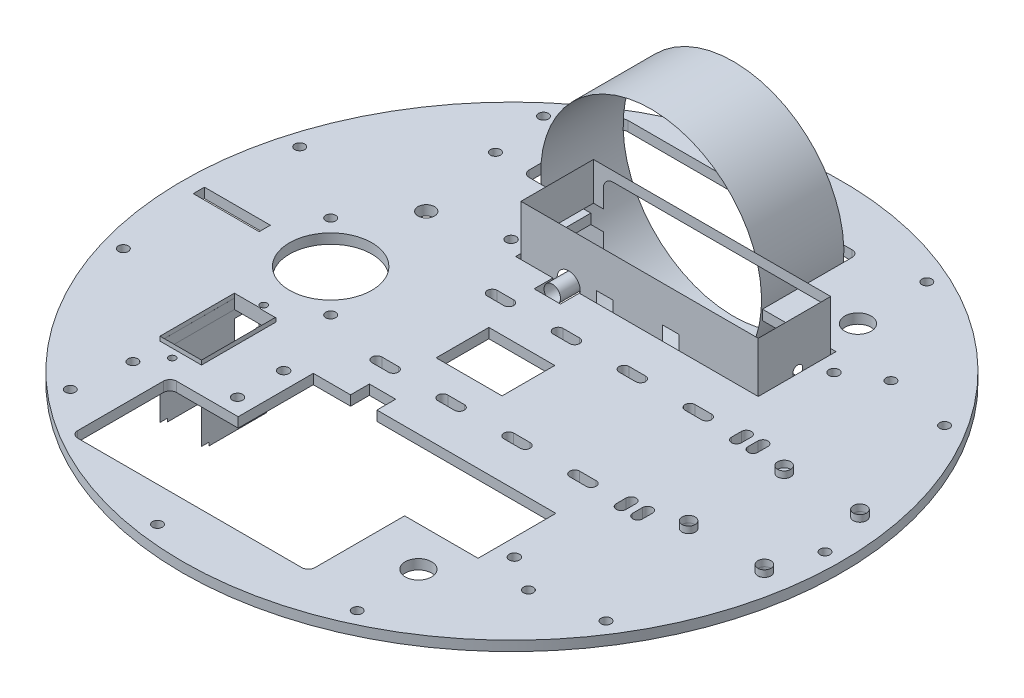
SolidWorks part; units mm, degrees
ref_plane "前基準面" through (0, 0, 0) normal (0, 0, 1) x (1, 0, 0)
ref_plane "上基準面" through (0, 0, 0) normal (0, 1, 0) x (1, 0, 0)
ref_plane "右基準面" through (0, 0, 0) normal (1, 0, 0) x (0, 0, -1)
sketch "草圖2" plane through (0, 0, 0) normal (0, 1, 0) x (1, 0, 0)
  line L1 (-60, 60) -> (60, 60) construction
  line L2 (-60, 60) -> (-60, -60) construction
  line L3 (-60, -60) -> (60, -60) construction
  line L4 (60, 60) -> (60, -60) construction
  line L5 (-60, 60) -> (60, -60) construction
  line L6 (-60, -60) -> (60, 60) construction
  circle A1 centre (0, 0) radius 100
  point P0 (0, 0)
  dimension "D1" = 120
  dimension "D3" = 200
  dimension "D2" = 120
extrude "填料-伸長1" add sketch "草圖2" along normal blind 3
sketch "草圖4" plane through (0, 3, 0) normal (0, 1, 0) x (1, 0, 0)
  line L0 (0, 0) -> (-55, 0) construction
  circle A1 centre (-55, 0) radius 12.5
  dimension "D2" = 25
  dimension "D1" = 55
extrude "除料-伸長2" cut sketch "草圖4" against normal blind 3
sketch "草圖5" plane through (0, 3, 0) normal (0, 1, 0) x (1, 0, 0)
  line L1 (-60, 55) -> (60, 55) construction
  line L2 (-60, 55) -> (-60, -55) construction
  line L3 (-60, -55) -> (60, -55) construction
  line L4 (60, 55) -> (60, -55) construction
  line L5 (-60, 55) -> (60, -55) construction
  line L6 (-60, -55) -> (60, 55) construction
  circle A0 centre (-60, 55) radius 1.5
  circle A1 centre (-60, -55) radius 1.5
  circle A2 centre (60, -55) radius 1.5
  circle A3 centre (60, 55) radius 1.5
  point P0 (0, 0)
  dimension "D3" = 3
  dimension "D4" = 3
  dimension "D5" = 3
  dimension "D6" = 3
  dimension "D1" = 120
  dimension "D2" = 110
extrude "除料-伸長3" cut sketch "草圖5" against normal blind 3
sketch "草圖6" plane through (0, 3, 0) normal (0, 1, 0) x (1, 0, 0)
  line L0 (0, 0) -> (126.0142, -2.0364) construction
  circle A0 centre (40, 65) radius 4
  circle A1 centre (37.8789, -66.2585) radius 4
  dimension "D1" = 8
  dimension "D2" = 40
  dimension "D3" = 65
extrude "除料-伸長4" cut sketch "草圖6" against normal blind 10
sketch "草圖7" plane through (0, 3, 0) normal (0, 1, 0) x (1, 0, 0)
  line L0 (0, 0) -> (-120.1853, 0) construction
  circle A1 centre (-70, -43.1259) radius 2.3
  circle A2 centre (-70, 43.1259) radius 2.3
  dimension "D1" = 43.1259
  dimension "D2" = 43.1259
  dimension "D3" = 70
extrude "除料-伸長5" [suppressed] cut sketch "草圖7" against normal up to surface (3 mm away)
sketch "草圖8" plane through (0, 3, 0) normal (0, 1, 0) x (1, 0, 0)
  line L0 (0, 0) -> (-129.4635, 0) construction
  line L2 (-99.2157, 12.5) -> (-111.2157, 12.5)
  line L3 (-99.2157, 12.5) -> (-99.2157, -12.5)
  line L4 (-99.2157, -12.5) -> (-111.2157, -12.5)
  line L5 (-114.2157, 9.5) -> (-114.2157, -9.5)
  circle A0 centre (0, 0) radius 100 construction
  arc A1 (-111.2157, -12.5) -> (-114.2157, -9.5) centre (-111.2157, -9.5) cw
  arc A2 (-111.2157, 12.5) -> (-114.2157, 9.5) centre (-111.2157, 9.5) ccw
  point P13 (-114.2157, -12.5)
  point P16 (-114.2157, 12.5)
  dimension "D3" = 3
  dimension "D1" = 25
  dimension "D2" = 15
extrude "填料-伸長2" add sketch "草圖8" against normal up to surface (3 mm away) up to face at (40, 0, -61)
sketch "草圖9" plane through (0, 3, 0) normal (0, 1, 0) x (1, 0, 0)
  line L0 (0, 0) -> (-116.8069, 0) construction
  line L2 (-95, 1.7) -> (-75, 1.7)
  line L3 (-95, 1.7) -> (-95, -1.7)
  line L4 (-95, -1.7) -> (-75, -1.7)
  line L5 (-75, 1.7) -> (-75, -1.7)
  line L6 (-95, 1.7) -> (-75, -1.7) construction
  line L7 (-95, -1.7) -> (-75, 1.7) construction
  point P3 (-85, 0)
  dimension "D1" = 3.4
  dimension "D2" = 20
  dimension "D3" = 75
extrude "除料-伸長6" cut sketch "草圖9" against normal up to surface (3 mm away) up to face at (40, 0, -61)
sketch "草圖11" plane through (0, 3, 0) normal (0, 1, 0) x (1, 0, 0)
  line L0 (-114.2157, 0) -> (0, 0) construction
  line L1 (-114.2157, 9.5) -> (-114.2157, -9.5) construction
  line L2 (-55, 12.5) -> (-55, -12.5) construction
  circle A0 centre (-55, 0) radius 12.5 construction
  circle A1 centre (-55, -29) radius 2.5
  circle A2 centre (-55, 29) radius 2.5
  dimension "D1" = 5
  dimension "D2" = 29
  dimension "D3" = 0
extrude "除料-伸長9" cut sketch "草圖11" against normal blind 10
sketch "草圖12" plane through (0, 3, 0) normal (0, 1, 0) x (1, 0, 0)
  circle A0 centre (0, 0) radius 100
  circle A1 centre (0, 0) radius 174.0467
extrude "除料-伸長10" cut sketch "草圖12" against normal blind 10
surface "曲面-偏移1" parameters "D1"=0
sketch "草圖13" plane through (0, 3, 0) normal (0, 1, 0) x (1, 0, 0)
  line L0 (43.2344, 53.5) -> (43.2344, 31.5) construction
  line L1 (-28.7656, 53.5) -> (43.2344, 53.5) construction
  line L2 (-28.7656, 31.5) -> (-28.7656, 53.5) construction
  line L3 (43.2344, 31.5) -> (-28.7656, 31.5) construction
  line L4 (43.2344, 53.5) -> (43.2344, 31.5) construction
  line L5 (21.7344, 53.5) -> (43.2344, 53.5) construction
  line L6 (-28.7656, 31.5) -> (-28.7656, 53.5) construction
  line L7 (43.2344, 31.5) -> (-18.2656, 31.5) construction
  line L8 (-16.7656, 33.5) -> (-16.7656, 26.5) construction
  line L10 (-18.2656, 30.7) -> (-18.2656, 25)
  line L11 (-18.2656, 25) -> (-10.2656, 25)
  line L12 (-10.2656, 30.7) -> (-10.2656, 25)
  line L14 (19.2344, 81.5) -> (-47.7656, 81.5) construction
  line L15 (-50.2656, 53.5) -> (-29.5656, 53.5)
  line L16 (-50.2656, 53.5) -> (-50.2656, 83.5)
  line L17 (-50.2656, 83.5) -> (21.7344, 83.5)
  line L18 (21.7344, 54.3) -> (21.7344, 83.5)
  line L19 (-47.7656, 56.5) -> (19.2344, 56.5) construction
  line L20 (-47.7656, 56.5) -> (19.2344, 56.5) construction
  line L21 (19.2344, 81.5) -> (-47.7656, 81.5) construction
  line L22 (0, 0) -> (91.0786, 0) construction
  line L23 (21.7344, -53.5) -> (43.2344, -53.5) construction
  line L24 (-28.7656, -31.5) -> (-28.7656, -53.5) construction
  line L25 (43.2344, -31.5) -> (-28.7656, -31.5) construction
  line L26 (43.2344, -53.5) -> (43.2344, -31.5) construction
  line L27 (-50.2656, -83.5) -> (21.7344, -83.5)
  line L28 (21.7344, -54.3) -> (21.7344, -83.5)
  line L29 (-50.2656, -53.5) -> (-29.5656, -53.5)
  line L30 (-50.2656, -53.5) -> (-50.2656, -83.5)
  line L31 (44.0344, 30.7) -> (-10.2656, 30.7)
  line L32 (-29.5656, 30.7) -> (-29.5656, 53.5)
  line L33 (21.7344, 54.3) -> (44.0344, 54.3)
  line L34 (44.0344, 54.3) -> (44.0344, 30.7)
  line L35 (-28.7656, 53.5) -> (43.2344, 53.5) construction
  line L36 (-29.5656, -30.7) -> (-29.5656, -53.5)
  line L37 (21.7344, -54.3) -> (44.0344, -54.3)
  line L38 (44.0344, -54.3) -> (44.0344, -30.7)
  line L39 (44.0344, -30.7) -> (-29.5656, -30.7) construction
  line L40 (-28.7656, -53.5) -> (43.2344, -53.5) construction
  line L41 (-29.5656, 54.3) -> (44.0344, 54.3) construction
  line L42 (-29.5656, 30.7) -> (-29.5656, 54.3) construction
  line L43 (-29.5656, -54.3) -> (44.0344, -54.3) construction
  line L44 (-29.5656, -30.7) -> (-29.5656, -54.3) construction
  line L45 (-18.2656, 31.5) -> (-28.7656, 31.5) construction
  line L46 (43.2344, 31.5) -> (-28.7656, 31.5) construction
  line L47 (-10.2656, -30.7) -> (-10.2656, -25)
  line L48 (-18.2656, -25) -> (-10.2656, -25)
  line L49 (-18.2656, -30.7) -> (-18.2656, -25)
  line L50 (-18.2656, 30.7) -> (-29.5656, 30.7)
  line L51 (44.0344, 30.7) -> (-29.5656, 30.7) construction
  line L52 (-29.5656, -30.7) -> (-18.2656, -30.7)
  line L53 (-10.2656, -30.7) -> (44.0344, -30.7)
  circle A0 centre (-34.7656, 34.5) radius 1.55 construction
  circle A1 centre (49.2344, 48.5) radius 1.55 construction
  circle A2 centre (-34.7656, 34.5) radius 1.55 construction
  circle A3 centre (-34.7656, 48.5) radius 1.55 construction
  circle A4 centre (-34.7656, 34.5) radius 1.55
  circle A5 centre (49.2344, 48.5) radius 1.55
  circle A6 centre (-34.7656, 34.5) radius 1.55
  circle A7 centre (-34.7656, 48.5) radius 1.55
  circle A8 centre (-34.7656, -34.5) radius 1.55
  circle A9 centre (49.2344, -48.5) radius 1.55
  circle A10 centre (-34.7656, -34.5) radius 1.55
  circle A11 centre (-34.7656, -48.5) radius 1.55
  dimension "D1" = 1.5
  dimension "D3" = 8
  dimension "D4" = 2
  dimension "D5" = 72
  dimension "D6" = 2.5
  dimension "D7" = 0.8
  dimension "D8" = 0.8
extrude "除料-伸長12" cut sketch "草圖13" against normal blind 3
surface "曲面-偏移2" parameters "D1"=0
sketch "草圖14" plane through (0, 3, 0) normal (0, 1, 0) x (1, 0, 0)
  circle A0 centre (91.0992, 14.5) radius 2 construction
  circle A1 centre (91.0992, -14.5) radius 2 construction
  circle A2 centre (68.0992, -14.5) radius 2 construction
  circle A3 centre (91.0992, -14.5) radius 2 construction
  circle A4 centre (91.0992, 14.5) radius 2
  circle A5 centre (91.0992, -14.5) radius 2
  circle A6 centre (68.0992, -14.5) radius 2
  circle A7 centre (91.0992, -14.5) radius 2
sketch "草圖16" plane through (0, 3, 0) normal (0, 1, 0) x (1, 0, 0)
  line L1 (-61.2924, -22.8971) -> (-48.7028, -22.8971)
  line L2 (-61.2924, -22.8971) -> (-61.2924, -45.5029)
  line L3 (-61.2924, -45.5029) -> (-48.7028, -45.5029)
  line L4 (-48.7028, -22.8971) -> (-48.7028, -45.5029)
  arc A0 (-54.3908, -48.9614) -> (-55.5908, -48.962) centre (-54.9912, -48.1) ccw construction
  arc A1 (-55.6044, -19.4386) -> (-54.4044, -19.438) centre (-55.004, -20.3) ccw construction
  arc A2 (-54.3908, -48.9614) -> (-55.5908, -48.962) centre (-54.9912, -48.1) ccw
  arc A3 (-55.6044, -19.4386) -> (-54.4044, -19.438) centre (-55.004, -20.3) ccw
  circle A4 centre (-55.004, -20.3) radius 1.05
  circle A5 centre (-54.9912, -48.1) radius 1.05
  circle M24 centre (-55, -29) radius 2.5
extrude "除料-伸長14" cut sketch "草圖16" against normal blind 3 contours L4 L1 L2 L3 M24 | A2 A5 | A3 A4
sketch "草圖17" plane through (0, 0, 0) normal (0, -1, 0) x (1, 0, 0)
  line L4 (25.5633, 13) -> (25.5633, 22) construction
  line L8 (25.5633, 13) -> (25.5633, 22) construction
  line L9 (25.5633, 22) -> (5.5633, 22) construction
  line L10 (5.5633, 22) -> (5.5633, 13) construction
  line L11 (5.5633, 13) -> (25.5633, 13) construction
  line L12 (25.5633, 13) -> (25.5633, 22) construction
  line L13 (25.5633, 22) -> (5.5633, 22) construction
  line L14 (5.5633, 22) -> (5.5633, 13) construction
  line L15 (5.5633, 13) -> (25.5633, 13) construction
  line L16 (25.5633, 17.5) -> (-33.0085, 17.5) construction
  line L17 (25.5633, 17.5) -> (-33.0085, 17.5) construction
  line L18 (36.5344, 17.5) -> (41.5344, 17.5) construction
  line L19 (36.5344, 19) -> (41.5344, 19)
  line L20 (36.5344, 16) -> (41.5344, 16)
  line L21 (44.0344, 54.3) -> (44.0344, 30.7) construction
  line L22 (16.5344, 16) -> (21.5344, 16)
  line L23 (16.5344, 19) -> (21.5344, 19)
  line L24 (16.5344, 17.5) -> (21.5344, 17.5) construction
  line L25 (-3.4656, 16) -> (1.5344, 16)
  line L26 (-3.4656, 19) -> (1.5344, 19)
  line L27 (-3.4656, 17.5) -> (1.5344, 17.5) construction
  line L28 (-23.4656, 16) -> (-18.4656, 16)
  line L29 (-23.4656, 19) -> (-18.4656, 19)
  line L30 (-23.4656, 17.5) -> (-18.4656, 17.5) construction
  line L31 (0, 0) -> (20.4182, 0) construction
  line L32 (36.5344, -17.5) -> (41.5344, -17.5) construction
  line L33 (36.5344, -19) -> (41.5344, -19)
  line L34 (36.5344, -16) -> (41.5344, -16)
  line L35 (16.5344, -17.5) -> (21.5344, -17.5) construction
  line L36 (16.5344, -19) -> (21.5344, -19)
  line L37 (16.5344, -16) -> (21.5344, -16)
  line L38 (-3.4656, -17.5) -> (1.5344, -17.5) construction
  line L39 (-3.4656, -19) -> (1.5344, -19)
  line L40 (-3.4656, -16) -> (1.5344, -16)
  line L41 (-23.4656, -17.5) -> (-18.4656, -17.5) construction
  line L42 (-23.4656, -19) -> (-18.4656, -19)
  line L43 (-23.4656, -16) -> (-18.4656, -16)
  arc A0 (36.5344, 19) -> (36.5344, 16) centre (36.5344, 17.5) ccw
  arc A1 (41.5344, 16) -> (41.5344, 19) centre (41.5344, 17.5) ccw
  arc A2 (16.5344, 19) -> (16.5344, 16) centre (16.5344, 17.5) ccw
  arc A3 (21.5344, 16) -> (21.5344, 19) centre (21.5344, 17.5) ccw
  arc A4 (-3.4656, 19) -> (-3.4656, 16) centre (-3.4656, 17.5) ccw
  arc A5 (1.5344, 16) -> (1.5344, 19) centre (1.5344, 17.5) ccw
  arc A6 (-23.4656, 19) -> (-23.4656, 16) centre (-23.4656, 17.5) ccw
  arc A7 (-18.4656, 16) -> (-18.4656, 19) centre (-18.4656, 17.5) ccw
  arc A8 (36.5344, -19) -> (36.5344, -16) centre (36.5344, -17.5) cw
  arc A9 (41.5344, -16) -> (41.5344, -19) centre (41.5344, -17.5) cw
  arc A10 (16.5344, -19) -> (16.5344, -16) centre (16.5344, -17.5) cw
  arc A11 (21.5344, -16) -> (21.5344, -19) centre (21.5344, -17.5) cw
  arc A12 (-3.4656, -19) -> (-3.4656, -16) centre (-3.4656, -17.5) cw
  arc A13 (1.5344, -16) -> (1.5344, -19) centre (1.5344, -17.5) cw
  arc A14 (-23.4656, -19) -> (-23.4656, -16) centre (-23.4656, -17.5) cw
  arc A15 (-18.4656, -16) -> (-18.4656, -19) centre (-18.4656, -17.5) cw
  point P15 (39.0344, 17.5)
  point P25 (19.0344, 17.5)
  point P33 (-0.9656, 17.5)
  point P40 (-20.9656, 17.5)
  point P48 (39.0344, -17.5)
  point P55 (19.0344, -17.5)
  point P62 (-0.9656, -17.5)
  point P69 (-20.9656, -17.5)
  dimension "D3" = 1.5
  dimension "D1" = 3
  dimension "D2" = 5
  dimension "D4" = 5
  dimension "D5" = 4
extrude "除料-伸長15" cut sketch "草圖17" against normal blind 3
sketch "草圖18" plane through (0, 0, 0) normal (0, -1, 0) x (1, 0, 0)
  line L1 (5, -8) -> (-15, -8)
  line L2 (5, -8) -> (5, 8)
  line L3 (5, 8) -> (-15, 8)
  line L4 (-15, -8) -> (-15, 8)
  point P0 (0, 0)
  dimension "D1" = 8
  dimension "D2" = 8
  dimension "D3" = 20
  dimension "D4" = 5
extrude "除料-伸長16" cut sketch "草圖18" against normal blind 3
sketch "草圖19" plane through (0, 3, 0) normal (0, 1, 0) x (1, 0, 0)
  line L0 (-55, 0) -> (-74.1044, 19.1044) construction
  line L1 (-55, 0) -> (0, 0) construction
  line L2 (-55, 0) -> (-35.7867, -19.2133) construction
  circle A0 centre (-67.7279, 12.7279) radius 1.5
  circle A1 centre (-42.2721, -12.7279) radius 1.5
  dimension "D2" = 3
  dimension "D3" = 3
  dimension "D1" = 135
  dimension "D4" = 18
  dimension "D5" = 18
extrude "除料-伸長17" cut sketch "草圖19" against normal blind 3
sketch "草圖20" plane through (0, 0, 0) normal (0, -1, 0) x (1, 0, 0)
  circle A0 centre (0, 0) radius 95 construction
  circle A1 centre (95, 0) radius 1.5
  circle A2 centre (79.9191, -51.3609) radius 1.5
  circle A3 centre (39.4644, -86.415) radius 1.5
  circle A4 centre (-13.5199, -94.033) radius 1.5
  circle A5 centre (-62.2118, -71.7962) radius 1.5
  circle A6 centre (-91.1518, -26.7646) radius 1.5
  circle A7 centre (-91.1518, 26.7646) radius 1.5
  circle A8 centre (-62.2118, 71.7962) radius 1.5
  circle A9 centre (-13.5199, 94.033) radius 1.5
  circle A10 centre (39.4644, 86.415) radius 1.5
  circle A11 centre (79.9191, 51.3609) radius 1.5
  point P27 (0, 0)
  dimension "D1" = 190
  dimension "D2" = 3
  dimension "D3" = 11
extrude "除料-伸長18" cut sketch "草圖20" against normal blind 3
sketch "草圖21" plane through (0, 0, 0) normal (0, -1, 0) x (1, 0, 0)
  line L0 (52.142, -19) -> (52.142, -16) construction
  line L1 (50.642, -19) -> (50.642, -16)
  line L2 (53.642, -19) -> (53.642, -16)
  line L3 (57.142, -19) -> (57.142, -16) construction
  line L4 (55.642, -19) -> (55.642, -16)
  line L5 (58.642, -19) -> (58.642, -16)
  line L6 (52.142, -17.5) -> (57.142, -17.5) construction
  line L7 (0, 0) -> (80.616, 0) construction
  line L8 (39.0344, -16) -> (39.0344, -19) construction
  line L9 (41.5344, -16) -> (36.5344, -16) construction
  line L10 (36.5344, -19) -> (41.5344, -19) construction
  line L11 (39.0344, -17.5) -> (48.889, -17.5) construction
  line L12 (57.142, 19) -> (57.142, 16) construction
  line L13 (55.642, 19) -> (55.642, 16)
  line L14 (58.642, 19) -> (58.642, 16)
  line L15 (52.142, 19) -> (52.142, 16) construction
  line L16 (50.642, 19) -> (50.642, 16)
  line L17 (53.642, 19) -> (53.642, 16)
  arc A0 (50.642, -19) -> (53.642, -19) centre (52.142, -19) ccw
  arc A1 (53.642, -16) -> (50.642, -16) centre (52.142, -16) ccw
  arc A2 (55.642, -19) -> (58.642, -19) centre (57.142, -19) ccw
  arc A3 (58.642, -16) -> (55.642, -16) centre (57.142, -16) ccw
  arc A4 (55.642, 19) -> (58.642, 19) centre (57.142, 19) cw
  arc A5 (58.642, 16) -> (55.642, 16) centre (57.142, 16) cw
  arc A6 (50.642, 19) -> (53.642, 19) centre (52.142, 19) cw
  arc A7 (53.642, 16) -> (50.642, 16) centre (52.142, 16) cw
  point P2 (52.142, -17.5)
  point P7 (53.642, -17.5)
  point P10 (57.142, -17.5)
  point P31 (57.142, 17.5)
  point P38 (52.142, 17.5)
  dimension "D1" = 3
  dimension "D2" = 3
  dimension "D3" = 5
  dimension "D4" = 3
  dimension "D5" = 3
extrude "除料-伸長19" cut sketch "草圖21" against normal blind 3
fillet "圓角1" radius 2 6 edges at (21.7344, 1.5, 83.5) (-50.2656, 1.5, 83.5) (-50.2656, 1.5, 53.5) (21.7344, 1.5, -83.5) (-50.2656, 1.5, -53.5) (-50.2656, 1.5, -83.5)
extrude "除料-伸長21" cut sketch "草圖14" against normal blind 10 contours A4 | A5 | A6
